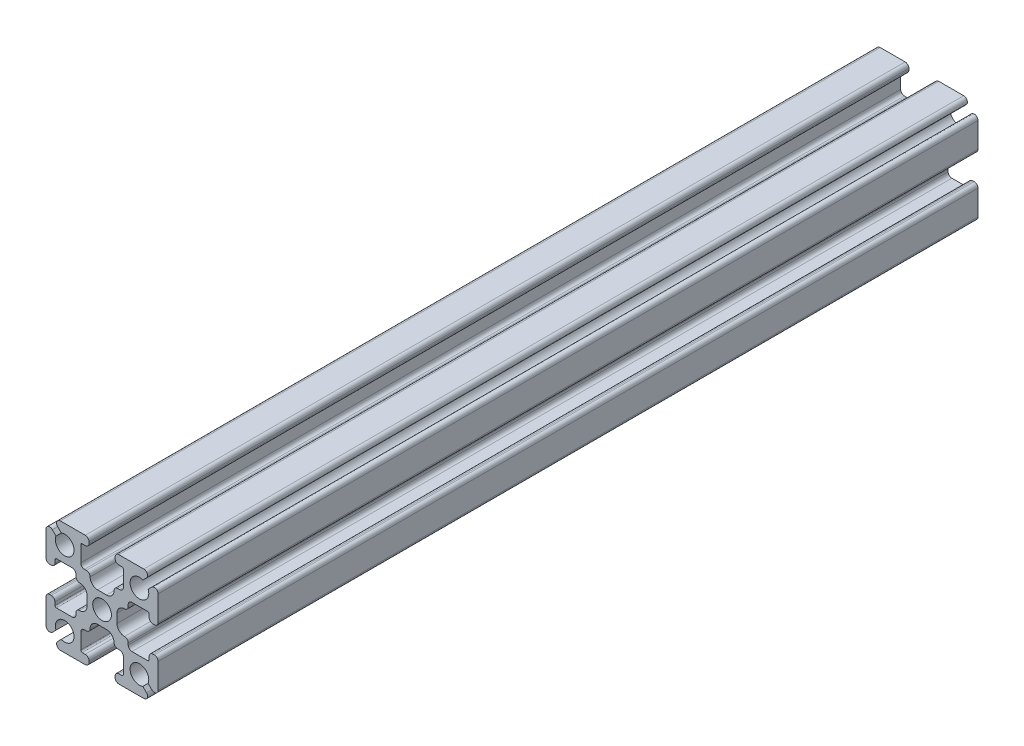
SolidWorks part; units mm, degrees
ref_plane "Front" through (0, 0, 0) normal (0, 0, 1) x (1, 0, 0)
ref_plane "Top" through (0, 0, 0) normal (0, 1, 0) x (1, 0, 0)
ref_plane "Right" through (0, 0, 0) normal (1, 0, 0) x (0, 0, -1)
sketch "Sketch1" plane through (0, 0, 0) normal (0, 0, 1) x (1, 0, 0)
  line L0 (6.6464, 5.9393) -> (6.1636, 5.4565)
  line L1 (5.4565, 6.1636) -> (5.9393, 6.6464)
  line L2 (5.5858, 7.5) -> (2.25, 7.5)
  line L3 (1.75, 7) -> (1.75, 6.8)
  line L4 (2.25, 6.3) -> (2.65, 6.3)
  line L5 (2.85, 6.1) -> (2.85, 4)
  line L6 (2.35, 3.5) -> (2.1, 3.5)
  line L7 (0.6, 2) -> (-0.6, 2)
  line L8 (-2.1, 3.5) -> (-2.35, 3.5)
  line L9 (-2.85, 4) -> (-2.85, 6.1)
  line L10 (-2.65, 6.3) -> (-2.25, 6.3)
  line L11 (-1.75, 6.8) -> (-1.75, 7)
  line L12 (-2.25, 7.5) -> (-5.5858, 7.5)
  line L13 (-5.9393, 6.6464) -> (-5.4565, 6.1636)
  line L14 (-6.1636, 5.4565) -> (-6.6464, 5.9393)
  line L15 (-7.5, 5.5858) -> (-7.5, 2.25)
  line L16 (-7, 1.75) -> (-6.8, 1.75)
  line L17 (-6.3, 2.25) -> (-6.3, 2.65)
  line L18 (-6.1, 2.85) -> (-4, 2.85)
  line L19 (-3.5, 2.35) -> (-3.5, 2.1)
  line L20 (-2, 0.6) -> (-2, -0.6)
  line L21 (-3.5, -2.1) -> (-3.5, -2.35)
  line L22 (-4, -2.85) -> (-6.1, -2.85)
  line L23 (-6.3, -2.65) -> (-6.3, -2.25)
  line L24 (-6.8, -1.75) -> (-7, -1.75)
  line L25 (-7.5, -2.25) -> (-7.5, -5.5858)
  line L26 (-6.6464, -5.9393) -> (-6.1636, -5.4565)
  line L27 (-5.4565, -6.1636) -> (-5.9393, -6.6464)
  line L28 (-5.5858, -7.5) -> (-2.25, -7.5)
  line L29 (-1.75, -7) -> (-1.75, -6.8)
  line L30 (-2.25, -6.3) -> (-2.65, -6.3)
  line L31 (-2.85, -6.1) -> (-2.85, -4)
  line L32 (-2.35, -3.5) -> (-2.1, -3.5)
  line L33 (-0.6, -2) -> (0.6, -2)
  line L34 (2.1, -3.5) -> (2.35, -3.5)
  line L35 (2.85, -4) -> (2.85, -6.1)
  line L36 (2.65, -6.3) -> (2.25, -6.3)
  line L37 (1.75, -6.8) -> (1.75, -7)
  line L38 (2.25, -7.5) -> (5.5858, -7.5)
  line L39 (5.9393, -6.6464) -> (5.4565, -6.1636)
  line L40 (6.1636, -5.4565) -> (6.6464, -5.9393)
  line L41 (7.5, -5.5858) -> (7.5, -2.25)
  line L42 (7, -1.75) -> (6.8, -1.75)
  line L43 (6.3, -2.25) -> (6.3, -2.65)
  line L44 (6.1, -2.85) -> (4, -2.85)
  line L45 (3.5, -2.35) -> (3.5, -2.1)
  line L46 (2, -0.6) -> (2, 0.6)
  line L47 (3.5, 2.1) -> (3.5, 2.35)
  line L48 (4, 2.85) -> (6.1, 2.85)
  line L49 (6.3, 2.65) -> (6.3, 2.25)
  line L50 (6.8, 1.75) -> (7, 1.75)
  line L51 (7.5, 2.25) -> (7.5, 5.5858)
  circle A0 centre (0, 0) radius 1.25
  arc A1 (6.1636, 5.4565) -> (5.4565, 6.1636) centre (5, 5) cw
  arc A2 (5.9393, 6.6464) -> (5.5858, 7.5) centre (5.5858, 7) ccw
  arc A3 (2.25, 7.5) -> (1.75, 7) centre (2.25, 7) ccw
  arc A4 (1.75, 6.8) -> (2.25, 6.3) centre (2.25, 6.8) ccw
  arc A5 (2.65, 6.3) -> (2.85, 6.1) centre (2.65, 6.1) cw
  arc A6 (2.85, 4) -> (2.35, 3.5) centre (2.35, 4) cw
  arc A7 (2.1, 3.5) -> (1.6, 3) centre (2.1, 3) ccw
  arc A8 (1.6, 3) -> (0.6, 2) centre (0.6, 3) cw
  arc A9 (-0.6, 2) -> (-1.6, 3) centre (-0.6, 3) cw
  arc A10 (-1.6, 3) -> (-2.1, 3.5) centre (-2.1, 3) ccw
  arc A11 (-2.35, 3.5) -> (-2.85, 4) centre (-2.35, 4) cw
  arc A12 (-2.85, 6.1) -> (-2.65, 6.3) centre (-2.65, 6.1) cw
  arc A13 (-2.25, 6.3) -> (-1.75, 6.8) centre (-2.25, 6.8) ccw
  arc A14 (-1.75, 7) -> (-2.25, 7.5) centre (-2.25, 7) ccw
  arc A15 (-5.5858, 7.5) -> (-5.9393, 6.6464) centre (-5.5858, 7) ccw
  arc A16 (-5.4565, 6.1636) -> (-6.1636, 5.4565) centre (-5, 5) cw
  arc A17 (-6.6464, 5.9393) -> (-7.5, 5.5858) centre (-7, 5.5858) ccw
  arc A18 (-7.5, 2.25) -> (-7, 1.75) centre (-7, 2.25) ccw
  arc A19 (-6.8, 1.75) -> (-6.3, 2.25) centre (-6.8, 2.25) ccw
  arc A20 (-6.3, 2.65) -> (-6.1, 2.85) centre (-6.1, 2.65) cw
  arc A21 (-4, 2.85) -> (-3.5, 2.35) centre (-4, 2.35) cw
  arc A22 (-3.5, 2.1) -> (-3, 1.6) centre (-3, 2.1) ccw
  arc A23 (-3, 1.6) -> (-2, 0.6) centre (-3, 0.6) cw
  arc A24 (-2, -0.6) -> (-3, -1.6) centre (-3, -0.6) cw
  arc A25 (-3, -1.6) -> (-3.5, -2.1) centre (-3, -2.1) ccw
  arc A26 (-3.5, -2.35) -> (-4, -2.85) centre (-4, -2.35) cw
  arc A27 (-6.1, -2.85) -> (-6.3, -2.65) centre (-6.1, -2.65) cw
  arc A28 (-6.3, -2.25) -> (-6.8, -1.75) centre (-6.8, -2.25) ccw
  arc A29 (-7, -1.75) -> (-7.5, -2.25) centre (-7, -2.25) ccw
  arc A30 (-7.5, -5.5858) -> (-6.6464, -5.9393) centre (-7, -5.5858) ccw
  arc A31 (-6.1636, -5.4565) -> (-5.4565, -6.1636) centre (-5, -5) cw
  arc A32 (-5.9393, -6.6464) -> (-5.5858, -7.5) centre (-5.5858, -7) ccw
  arc A33 (-2.25, -7.5) -> (-1.75, -7) centre (-2.25, -7) ccw
  arc A34 (-1.75, -6.8) -> (-2.25, -6.3) centre (-2.25, -6.8) ccw
  arc A35 (-2.65, -6.3) -> (-2.85, -6.1) centre (-2.65, -6.1) cw
  arc A36 (-2.85, -4) -> (-2.35, -3.5) centre (-2.35, -4) cw
  arc A37 (-2.1, -3.5) -> (-1.6, -3) centre (-2.1, -3) ccw
  arc A38 (-1.6, -3) -> (-0.6, -2) centre (-0.6, -3) cw
  arc A39 (0.6, -2) -> (1.6, -3) centre (0.6, -3) cw
  arc A40 (1.6, -3) -> (2.1, -3.5) centre (2.1, -3) ccw
  arc A41 (2.35, -3.5) -> (2.85, -4) centre (2.35, -4) cw
  arc A42 (2.85, -6.1) -> (2.65, -6.3) centre (2.65, -6.1) cw
  arc A43 (2.25, -6.3) -> (1.75, -6.8) centre (2.25, -6.8) ccw
  arc A44 (1.75, -7) -> (2.25, -7.5) centre (2.25, -7) ccw
  arc A45 (5.5858, -7.5) -> (5.9393, -6.6464) centre (5.5858, -7) ccw
  arc A46 (5.4565, -6.1636) -> (6.1636, -5.4565) centre (5, -5) cw
  arc A47 (6.6464, -5.9393) -> (7.5, -5.5858) centre (7, -5.5858) ccw
  arc A48 (7.5, -2.25) -> (7, -1.75) centre (7, -2.25) ccw
  arc A49 (6.8, -1.75) -> (6.3, -2.25) centre (6.8, -2.25) ccw
  arc A50 (6.3, -2.65) -> (6.1, -2.85) centre (6.1, -2.65) cw
  arc A51 (4, -2.85) -> (3.5, -2.35) centre (4, -2.35) cw
  arc A52 (3.5, -2.1) -> (3, -1.6) centre (3, -2.1) ccw
  arc A53 (3, -1.6) -> (2, -0.6) centre (3, -0.6) cw
  arc A54 (2, 0.6) -> (3, 1.6) centre (3, 0.6) cw
  arc A55 (3, 1.6) -> (3.5, 2.1) centre (3, 2.1) ccw
  arc A56 (3.5, 2.35) -> (4, 2.85) centre (4, 2.35) cw
  arc A57 (6.1, 2.85) -> (6.3, 2.65) centre (6.1, 2.65) cw
  arc A58 (6.3, 2.25) -> (6.8, 1.75) centre (6.8, 2.25) ccw
  arc A59 (7, 1.75) -> (7.5, 2.25) centre (7, 2.25) ccw
  arc A60 (7.5, 5.5858) -> (6.6464, 5.9393) centre (7, 5.5858) ccw
extrude "Boss-Extrude1" add sketch "Sketch1" along normal blind 109.7
